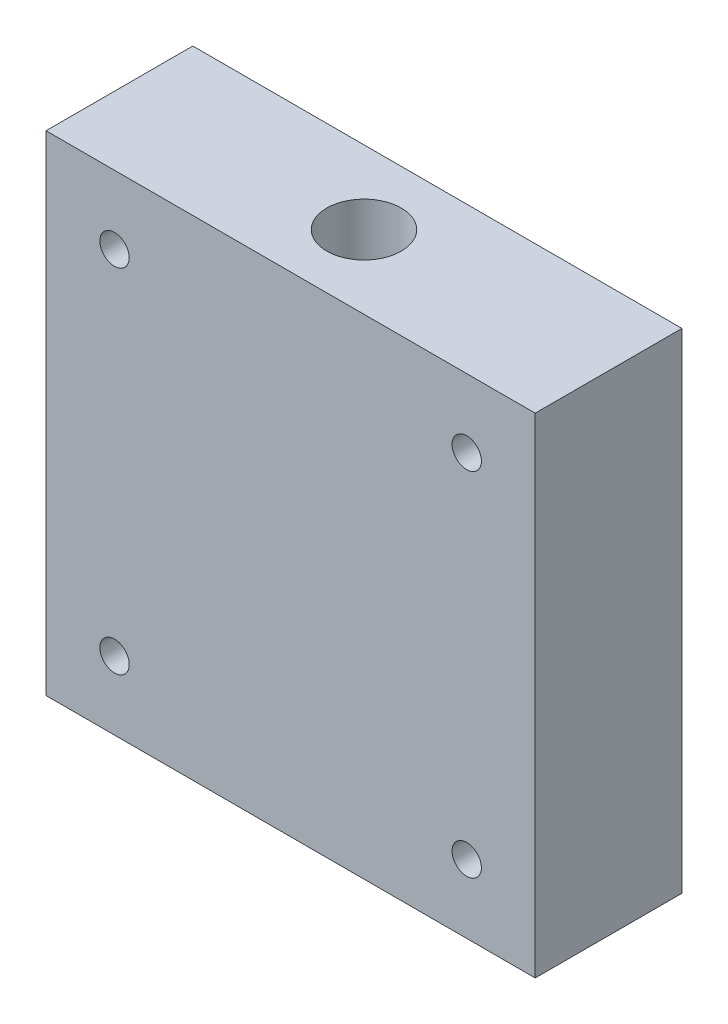
SolidWorks part; units mm, degrees
ref_plane "Plano frontal" through (0, 0, 0) normal (0, 0, 1) x (1, 0, 0)
ref_plane "Plano superior" through (0, 0, 0) normal (0, 1, 0) x (1, 0, 0)
ref_plane "Plano direito" through (0, 0, 0) normal (1, 0, 0) x (0, 0, -1)
sketch "Esboço1" plane through (0, 0, 0) normal (0, 0, 1) x (1, 0, 0)
  line L1 (25, -25) -> (-25, -25)
  line L2 (25, -25) -> (25, 25)
  line L3 (25, 25) -> (-25, 25)
  line L4 (-25, -25) -> (-25, 25)
  line L5 (25, -25) -> (-25, 25) construction
  line L6 (25, 25) -> (-25, -25) construction
  point P0 (0, 0)
  dimension "D1" = 50
  dimension "D2" = 50
extrude "Ressalto-extrusão1" add sketch "Esboço1" along normal blind 15
sketch "Esboço2" plane through (0, 25, 0) normal (0, 1, 0) x (1, 0, 0)
  line L1 (25, -15) -> (-25, -15) construction
  circle A0 centre (0, -7.5) radius 3.815
  dimension "D2" = 7.63
  dimension "D1" = 7.5
extrude "Corte-extrusão1" cut sketch "Esboço2" against normal blind 20
sketch "Esboço3" plane through (0, 0, 15) normal (0, 0, 1) x (1, 0, 0)
  line L0 (-25, 25) -> (-25, -25) construction
  line L1 (25, 25) -> (-25, 25) construction
  line L2 (-25, -25) -> (25, -25) construction
  line L3 (25, -25) -> (25, 25) construction
  circle A0 centre (-18, 18) radius 1.5
  circle A1 centre (-18, -18) radius 1.5
  circle A2 centre (18, 18) radius 1.5
  circle A3 centre (18, -18) radius 1.5
  point P6 (0, 0)
  dimension "D3" = 3
  dimension "D4" = 7
  dimension "D1" = 7
  dimension "D2" = 7
  dimension "D5" = 7
  dimension "D6" = 7
  dimension "D7" = 7
  dimension "D8" = 7
  dimension "D9" = 7
extrude "Corte-extrusão2" cut sketch "Esboço3" against normal through all
